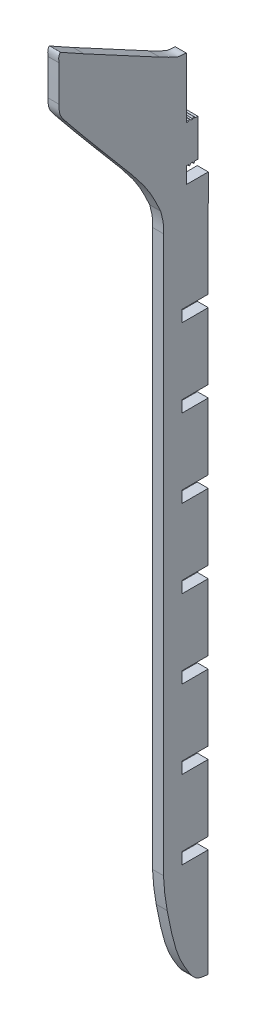
SolidWorks part; units mm, degrees
ref_plane "Alzado" through (0, 0, 0) normal (1, 0, 0) x (0, 1, 0)
ref_plane "Planta" through (0, 0, 0) normal (0, 0, 1) x (0, 1, 0)
ref_plane "Vista lateral" through (0, 0, 0) normal (0, 1, 0) x (-1, 0, 0)
sketch "Croquis1" plane through (0, 0, 0) normal (1, 0, 0) x (0, 1, 0)
  line L0 (69.8128, -8.4703) -> (69.8133, -7.6896)
  line L1 (69.8133, -7.2621) -> (69.8133, -6.6199)
  line L2 (69.8133, -6.1924) -> (69.8128, -5.6204)
  line L3 (78.989, -6.6281) -> (78.99, -7.2693)
  line L4 (78.9849, -7.6968) -> (78.9837, -8.4703)
  line L5 (78.9796, -5.6236) -> (78.9796, -6.2007)
  line L14 (78.9837, -8.4703) -> (69.8128, -8.4703)
  line L15 (69.8128, -5.6204) -> (65.8244, -5.6204)
  line L16 (65.8244, -5.6204) -> (65.8239, -11.0323)
  line L17 (65.8239, -11.0323) -> (39.7477, -11.0281)
  line L18 (39.7477, -11.0281) -> (39.7488, -4.5292)
  line L19 (39.7488, -4.5292) -> (36.8988, -4.5287)
  line L20 (36.8988, -4.5287) -> (36.8977, -11.0276)
  line L21 (36.8977, -11.0276) -> (20.4868, -11.0249)
  line L22 (20.4868, -11.0249) -> (20.4879, -4.5261)
  line L23 (20.4879, -4.5261) -> (17.6379, -4.5256)
  line L24 (17.6379, -4.5256) -> (17.6368, -11.0245)
  line L25 (17.6368, -11.0245) -> (1.226, -11.0218)
  line L26 (1.226, -11.0218) -> (1.2271, -4.5229)
  line L27 (1.2271, -4.5229) -> (-1.6229, -4.5225)
  line L28 (-1.6229, -4.5225) -> (-1.624, -11.0213)
  line L29 (-1.624, -11.0213) -> (-18.0347, -11.0187)
  line L30 (-18.0347, -11.0187) -> (-18.0337, -4.5198)
  line L31 (-18.0337, -4.5198) -> (-20.8837, -4.5193)
  line L32 (-20.8837, -4.5193) -> (-20.8847, -11.0182)
  line L33 (-20.8847, -11.0182) -> (-37.2955, -11.0155)
  line L34 (-37.2955, -11.0155) -> (-37.2945, -4.5167)
  line L35 (-37.2945, -4.5167) -> (-40.1445, -4.5162)
  line L36 (-40.1445, -4.5162) -> (-40.1455, -11.0151)
  line L37 (-40.1455, -11.0151) -> (-56.5564, -11.0124)
  line L38 (-56.5564, -11.0124) -> (-56.5554, -4.5135)
  line L39 (-56.5554, -4.5135) -> (-59.4054, -4.5131)
  line L40 (-59.4054, -4.5131) -> (-59.4064, -11.0119)
  line L41 (-59.4064, -11.0119) -> (-75.832, -11.0093)
  line L42 (-75.832, -11.0093) -> (-75.8315, -4.5101)
  line L43 (-75.8315, -4.5101) -> (-78.6815, -4.5099)
  line L44 (-78.6815, -4.5099) -> (-78.682, -11.0088)
  line L45 (-78.682, -11.0088) -> (-105.2388, -11.0088)
  line L46 (93.8682, -5.6187) -> (80.2135, -5.6236)
  line L47 (78.9796, -5.6236) -> (80.2135, -5.6236)
  line L48 (-78.6891, -0.0088) -> (58.1264, -0.0311)
  spline S0 degree 3 poles (69.8133, -7.6896) (69.7183, -7.6904) (69.5472, -7.6919) (69.4717, -7.5423) (69.4381, -7.4758) knots 0 0 0 0 0.555651 1 1 1 1
  spline S1 degree 3 poles (69.4381, -7.4758) (69.4859, -7.3937) (69.5719, -7.2458) (69.739, -7.2571) (69.8133, -7.2621) knots 0 0 0 0 0.555666 1 1 1 1
  spline S2 degree 3 poles (69.8133, -6.6199) (69.7183, -6.6207) (69.5472, -6.6222) (69.4717, -6.4726) (69.4381, -6.4061) knots 0 0 0 0 0.555587 1 1 1 1
  spline S3 degree 3 poles (69.4381, -6.4061) (69.4859, -6.324) (69.5719, -6.1761) (69.739, -6.1874) (69.8133, -6.1924) knots 0 0 0 0 0.555666 1 1 1 1
  spline S4 degree 3 poles (79.3594, -6.4061) (79.3135, -6.4894) (79.2308, -6.6391) (79.0634, -6.6315) (78.989, -6.6281) knots 0 0 0 0 0.555692 1 1 1 1
  spline S5 degree 3 poles (78.99, -7.2693) (79.085, -7.2696) (79.2561, -7.2701) (79.3299, -7.4206) (79.3626, -7.4874) knots 0 0 0 0 0.55566 1 1 1 1
  spline S6 degree 3 poles (79.3626, -7.4874) (79.3139, -7.5691) (79.2262, -7.7159) (79.0592, -7.7027) (78.9849, -7.6968) knots 0 0 0 0 0.555654 1 1 1 1
  spline S7 degree 3 poles (78.9796, -6.2007) (79.0746, -6.1978) (79.2456, -6.1925) (79.3244, -6.3404) (79.3594, -6.4061) knots 0 0 0 0 0.555675 1 1 1 1
  spline S8 degree 3 poles (-105.2388, -11.0088) (-105.1486, -9.9835) (-104.9788, -8.0524) (-103.4159, -6.9292) (-102.6829, -6.4024) knots 0 0 0 0 0.530982 1 1 1 1
  spline S9 degree 3 poles (-102.6829, -6.4024) (-101.3947, -5.6085) (-98.6946, -3.9446) (-93.2157, -2.2097) (-89.0983, -1.4129) (-86.6027, -0.9301) knots 0 0 0 0 0.264377 0.554144 1 1 1 1
  spline S10 degree 3 poles (-86.6027, -0.9301) (-84.9732, -0.6557) (-82.3498, -0.214) (-79.6949, -0.0652) (-78.6891, -0.0088) knots 0 0 0 0 0.621145 1 1 1 1
  spline S11 degree 3 poles (58.1264, -0.0311) (59.0469, -0.0322) (60.8125, -0.0345) (62.5075, 0.456) (63.3187, 0.6908) knots 0 0 0 0 0.521422 1 1 1 1
  spline S12 degree 3 poles (63.3187, 0.6908) (65.1438, 1.5345) (69.0688, 3.349) (75.4048, 8.3095) (79.9474, 12.2143) (82.7433, 14.6176) knots 0 0 0 0 0.250491 0.53869 1 1 1 1
  spline S13 degree 3 poles (82.7433, 14.6176) (85.0473, 16.5588) (88.7151, 19.6492) (92.442, 22.668) (93.8278, 23.7906) knots 0 0 0 0 0.628148 1 1 1 1
  spline S14 degree 3 poles (93.8278, 23.7906) (94.3265, 24.1995) (95.1356, 24.8631) (96.7075, 25.7289) (97.846, 25.6923) (98.5723, 25.6689) knots 0 0 0 0 0.367688 0.596621 1 1 1 1
  spline S15 degree 3 poles (98.5723, 25.6689) (100.247, 25.6781) (103.1859, 25.6941) (106.1248, 25.6765) (107.389, 25.6689) knots 0 0 0 0 0.569822 1 1 1 1
  spline S16 degree 3 poles (107.389, 25.6689) (108.0603, 25.7829) (108.7832, 25.9056) (109.5489, 25.4263) (109.4826, 25.302) (109.4449, 25.2313) knots 0 0 0 0 0.848773 0.913886 1 1 1 1
  spline S17 degree 3 poles (109.4449, 25.2313) (109.3709, 25.0954) (109.1051, 24.6068) (108.5227, 23.585) (107.5456, 21.822) (106.7649, 20.4091) (106.284, 19.5387) knots 0 0 0 0 0.07128 0.25626 0.541851 1 1 1 1
  spline S18 degree 3 poles (106.284, 19.5387) (105.3969, 17.9093) (103.4677, 14.3657) (100.766, 9.3609) (98.3055, 4.7812) (96.8977, 2.1103) (96.2605, 0.9014) knots 0 0 0 0 0.263007 0.571987 0.806271 1 1 1 1
  spline S19 degree 3 poles (96.2605, 0.9014) (95.8742, 0.1682) (95.2406, -1.0343) (94.5008, -2.6298) (93.9454, -3.699) (93.9884, -4.7023) (93.9142, -5.2683) (93.8682, -5.6187) knots 0 0 0 0 0.352337 0.57784 0.75657 0.849295 1 1 1 1
  point P12 (0, 0)
  dimension "D1" = 2.85
  dimension "D2" = 2.85
  dimension "D3" = 2.85
  dimension "D4" = 2.85
  dimension "D5" = 2.85
  dimension "D6" = 2.85
  dimension "D7" = 2.85
  dimension "D8" = 11
  dimension "D9" = 11
  dimension "D10" = 11
  dimension "D11" = 11
  dimension "D12" = 11
  dimension "D13" = 11
  dimension "D14" = 11
  dimension "D15" = 11
  dimension "D16" = 30.85
  dimension "D17" = 25.7
extrude "Saliente-Extruir1" add sketch "Croquis1" along normal blind 2.7
